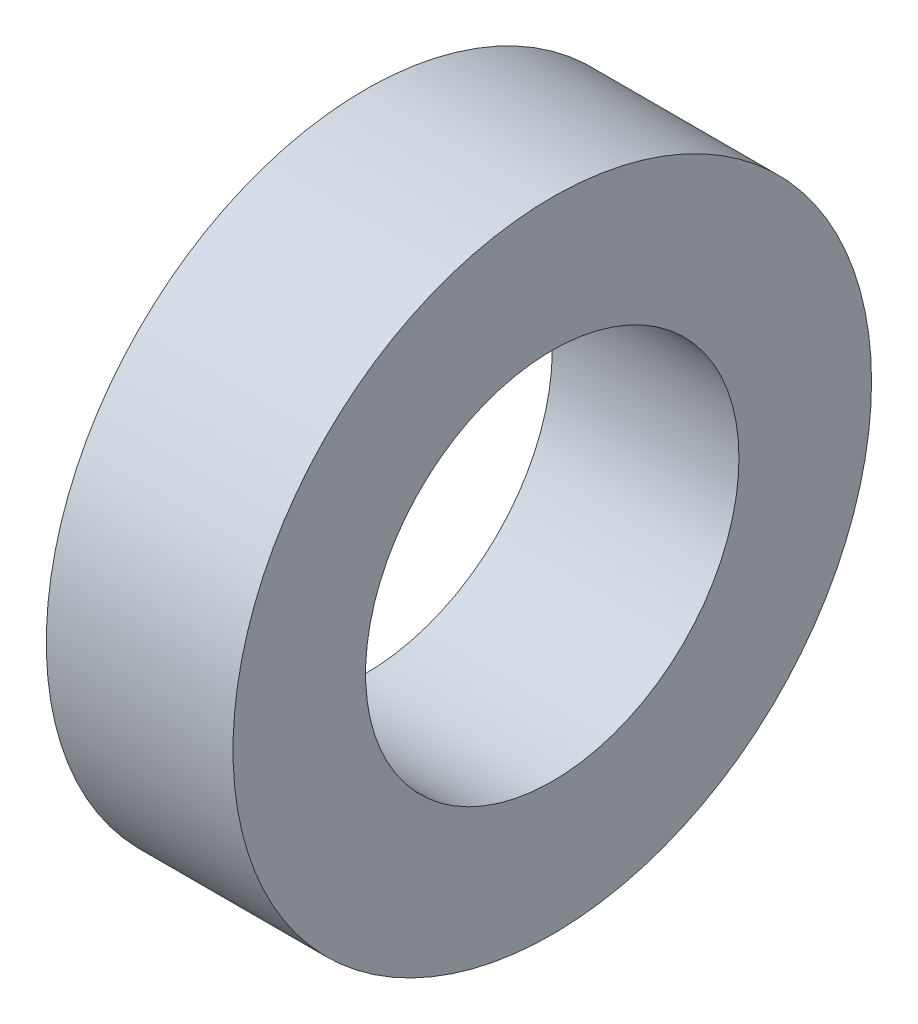
SolidWorks part; units mm, degrees
ref_plane "前视基准面" through (0, 0, 0) normal (0, 0, 1) x (1, 0, 0)
ref_plane "上视基准面" through (0, 0, 0) normal (0, 1, 0) x (1, 0, 0)
ref_plane "右视基准面" through (0, 0, 0) normal (1, 0, 0) x (0, 0, -1)
other "Configuration Table"
sketch "草图1" plane through (0, 0, 0) normal (1, 0, 0) x (0, 0, -1)
  circle A0 centre (0, 0) radius 8.55
  dimension "D1" = 17.1
extrude "凸台-拉伸1" add sketch "草图1" along normal blind 5
sketch "草图2" plane through (5, 0, 0) normal (1, 0, 0) x (0, 0, -1)
  circle A0 centre (0, 0) radius 5
  dimension "D1" = 10
extrude "切除-拉伸1" cut sketch "草图2" against normal blind 5
